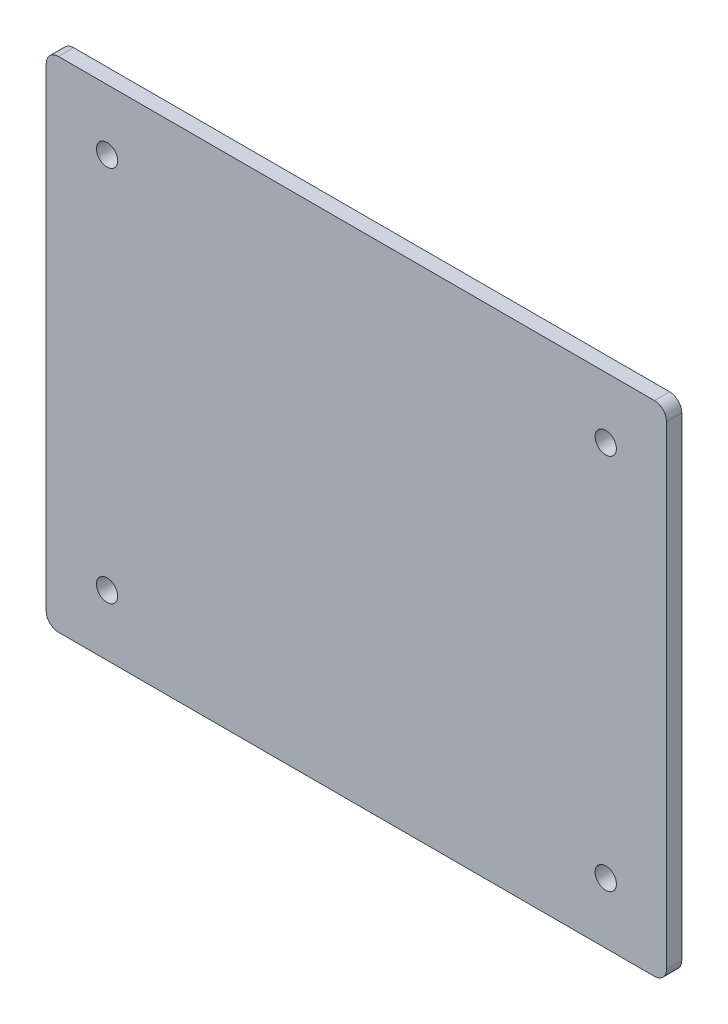
SolidWorks part; units mm, degrees
ref_plane "前基準面" through (0, 0, 0) normal (0, 0, 1) x (1, 0, 0)
ref_plane "上基準面" through (0, 0, 0) normal (0, 1, 0) x (1, 0, 0)
ref_plane "右基準面" through (0, 0, 0) normal (1, 0, 0) x (0, 0, -1)
sketch "草圖1" plane through (0, 0, 0) normal (0, 0, 1) x (1, 0, 0)
  line L0 (-45, 0) -> (45, 0) construction
  line L1 (-45, 35) -> (45, 35)
  line L2 (-45, 35) -> (-45, -35)
  line L3 (-45, -35) -> (45, -35)
  line L4 (45, 35) -> (45, -35)
  line L5 (0, 35) -> (0, -35) construction
  circle A0 centre (-41, 31) radius 1.75
  circle A1 centre (41, 31) radius 1.75
  circle A2 centre (41, -31) radius 1.75
  circle A3 centre (-41, -31) radius 1.75
  point P4 (0, 35)
  point P6 (-45, 0)
  dimension "D5" = 3.5
  dimension "D1" = 90
  dimension "D2" = 70
  dimension "D3" = 4
  dimension "D4" = 4
extrude "填料-伸長1" add sketch "草圖1" along normal blind 2.5
sketch "草圖2" plane through (0, 0, 2.5) normal (0, 0, 1) x (1, 0, 0)
  line L0 (-42.75, 31) -> (42.75, 31) construction
  line L1 (-51, 41) -> (51, 41)
  line L2 (-51, 41) -> (-51, -41)
  line L3 (-51, -41) -> (51, -41)
  line L4 (51, 41) -> (51, -41)
  line L5 (-41, 32.75) -> (-41, -32.75) construction
  line L6 (-42.75, -31) -> (42.75, -31) construction
  line L7 (41, 32.75) -> (41, -32.75) construction
  line L9 (-45, 35) -> (45, 35)
  line L10 (-45, 35) -> (-45, -35)
  line L11 (-45, -35) -> (45, -35)
  line L12 (45, 35) -> (45, -35)
  circle A0 centre (-41, 31) radius 1.75 construction
  circle A1 centre (41, 31) radius 1.75 construction
  circle A2 centre (-41, -31) radius 1.75 construction
  circle A3 centre (41, -31) radius 1.75 construction
  dimension "D1" = 10
  dimension "D2" = 10
  dimension "D3" = 10
  dimension "D4" = 10
extrude "填料-伸長2" add sketch "草圖2" against normal blind 2.5
fillet "圓角1" radius 2 4 edges at (51, -41, 1.25) (51, 41, 1.25) (-51, 41, 1.25) (-51, -41, 1.25)
